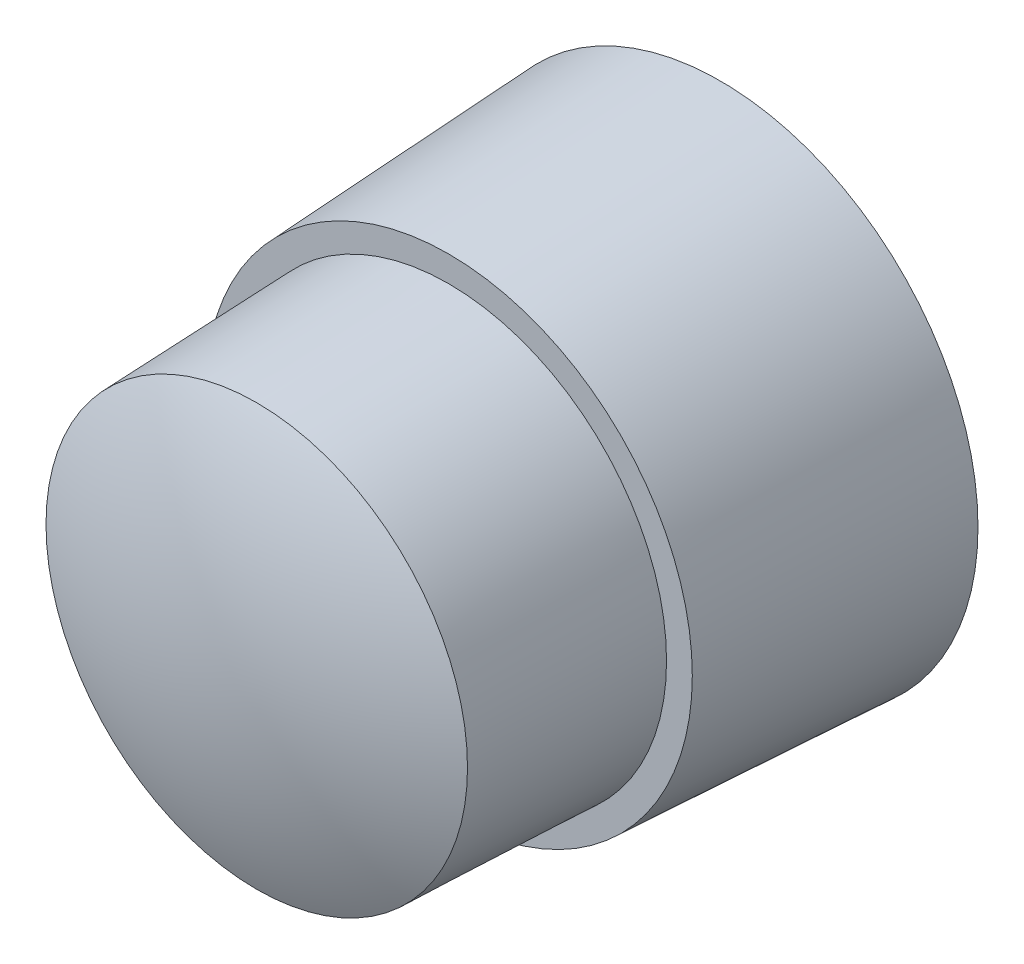
SolidWorks part; units mm, degrees
ref_plane "Front" through (0, 0, 0) normal (0, 0, 1) x (1, 0, 0)
ref_plane "Top" through (0, 0, 0) normal (0, 1, 0) x (1, 0, 0)
ref_plane "Right" through (0, 0, 0) normal (1, 0, 0) x (0, 0, -1)
sketch "Sketch3" plane through (0, 0, 0) normal (1, 0, 0) x (0, 0, -1)
  line L0 (0, 0) -> (0, 5.5)
  line L1 (0, 5.5) -> (-5.8, 5.2)
  line L2 (-5.8, 5.2) -> (-5.8, 0)
  line L3 (-5.8, 0) -> (0, 0)
  dimension "D1" = 5.5
  dimension "D2" = 5.8
  dimension "D3" = 5.2
revolve "Revolve1" add sketch "Sketch3" angle 360 about L3
sketch "Sketch5" plane through (0, 0, 0) normal (1, 0, 0) x (0, 0, -1)
  line L0 (-5.8, 5.2) -> (-5.8, -5.2) construction
  line L1 (-5.8, 5.2) -> (-5.8, -5.2) construction
  line L2 (-5.8, 4.65) -> (-9.9, 4.5)
  line L3 (-9.9, 4.5) -> (-9.9, 0)
  line L4 (-9.9, 0) -> (-5.8, 0)
  line L5 (-5.8, 0) -> (-5.8, 4.65)
  line L6 (0, 0) -> (-8.8329, 0) construction
  line L7 (0, -5.5) -> (0, 5.5) construction
  dimension "D1" = 4.65
  dimension "D2" = 4.5
  dimension "D3" = 9.9
revolve "Revolve2" add sketch "Sketch5" angle 360 about L4
sketch "Sketch6" plane through (0, 0, 0) normal (1, 0, 0) x (0, 0, -1)
  line L0 (0, 0) -> (-10.9, 0) construction
  line L1 (-10.9, 0) -> (-9.9, 0)
  line L2 (-9.9, 0) -> (-9.9, 4.5)
  line L3 (-10.9, 0) -> (-10.9, 5.3055) construction
  line L4 (0, -5.5) -> (0, 5.5) construction
  arc A0 (-9.9, 4.5) -> (-10.9, 0) centre (-0.275, 0) ccw
  dimension "D1" = 10.9
revolve "Revolve3" add sketch "Sketch6" angle 360 about L0
sketch "Sketch7" plane through (0, 0, 0) normal (0, 0, -1) x (-1, 0, 0)
  line L0 (0, 2.5885) -> (0, -2.4915) construction
  line L1 (-2.54, 0.0485) -> (2.54, 0.0485) construction
  circle A0 centre (0, 0.0485) radius 2.54 construction
  circle A1 centre (2.54, 0.0485) radius 0.225
  circle A2 centre (0, -2.4915) radius 0.225
  circle A3 centre (-2.54, 0.0485) radius 0.225
  dimension "D1" = 5.08
  dimension "D2" = 0.45
extrude "Boss-Extrude1" add sketch "Sketch7" along normal blind 2
